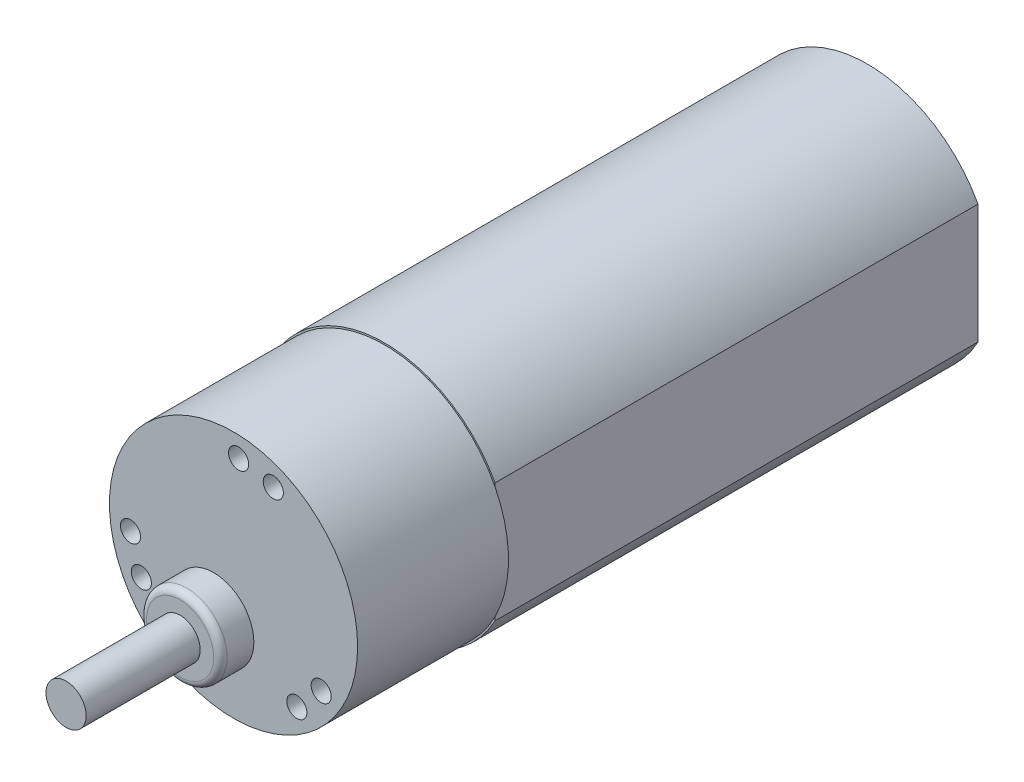
SolidWorks part; units mm, degrees
ref_plane "Front Plane" through (0, 0, 0) normal (0, 0, 1) x (1, 0, 0)
ref_plane "Top Plane" through (0, 0, 0) normal (0, 1, 0) x (1, 0, 0)
ref_plane "Right Plane" through (0, 0, 0) normal (1, 0, 0) x (0, 0, -1)
sketch "Sketch1" plane through (0, 0, 0) normal (0, 0, 1) x (1, 0, 0)
  line L0 (-16.5, 8.9058) -> (-16.5, -8.9058)
  line L1 (16.5, 8.9058) -> (16.5, -8.9058)
  arc A0 (-16.5, -8.9058) -> (16.5, -8.9058) centre (0, 0) ccw
  arc A1 (16.5, 8.9058) -> (-16.5, 8.9058) centre (0, 0) ccw
extrude "Boss-Extrude1" add sketch "Sketch1" along normal blind 72
sketch "Sketch2" plane through (0, 0, 72) normal (0, 0, 1) x (1, 0, 0)
  circle A0 centre (0, 0) radius 18.5
extrude "Boss-Extrude2" add sketch "Sketch2" along normal blind 22.5
sketch "Sketch3" plane through (0, 0, 94.5) normal (0, 0, 1) x (1, 0, 0)
  line L0 (0, 0) -> (-16.4075, -8.5466) construction
  line L1 (0.0271, -0.0522) -> (-13.7468, -7.1607) construction
  line L2 (0.0271, -0.0522) -> (0.7579, 15.4306) construction
  line L3 (0, 0) -> (-18.3411, -2.4195) construction
  line L4 (0, 0) -> (-15.3669, -2.0272) construction
  line L5 (-15.3669, -2.0272) -> (9.439, -12.2945) construction
  line L6 (5.9279, 14.3217) -> (-2.9639, -7.1608) construction
  circle A0 centre (0, 0) radius 18.5 construction
  circle A1 centre (-13.7468, -7.1607) radius 1.5
  circle A2 centre (0.7579, 15.4306) radius 1.5
  circle A3 centre (13.0701, -8.4265) radius 1.5
  circle A4 centre (-15.3669, -2.0272) radius 1.5
  circle A5 centre (5.9279, 14.3217) radius 1.5
  circle A6 centre (9.439, -12.2945) radius 1.5
  circle A7 centre (-2.9639, -7.1608) radius 6
  dimension "D1" = 3
  dimension "D6" = 3
  dimension "D3" = 120
  dimension "D4" = 15.5
  dimension "D5" = 20
  dimension "D8" = 15.5
  dimension "D2" = 3
  dimension "D7" = 3
extrude "Cut-Extrude1" cut sketch "Sketch3" against normal blind 5
sketch "Sketch4" plane through (0, 0, 89.5) normal (0, 0, 1) x (1, 0, 0)
  circle A0 centre (-2.9639, -7.1608) radius 6
extrude "Boss-Extrude3" add sketch "Sketch4" along normal blind 10
fillet "Fillet1" radius 1 1 edges at (3.0361, -7.1608, 99.5)
sketch "Sketch5" plane through (0, 0, 99.5) normal (0, 0, 1) x (1, 0, 0)
  circle A0 centre (-2.9639, -7.1608) radius 3
extrude "Boss-Extrude4" add sketch "Sketch5" along normal blind 17
sketch "Sketch6" plane through (-16.5, 0, 0) normal (-1, 0, 0) x (0, 0, 1)
  line L0 (72, -8.9058) -> (0, -8.9058) construction
  line L1 (0, 8.9058) -> (14.5455, 8.9058)
  line L2 (0, 8.9058) -> (0, -8.9058)
  line L3 (0, -8.9058) -> (14.5455, -8.9058)
  line L4 (14.5455, 8.9058) -> (14.5455, -8.9058)
extrude "Cut-Extrude2" cut sketch "Sketch6" against normal blind 7
sketch "Sketch7"
sketch_block_instance "Block2-1"
sketch_block "Block2"
sketch_block_instance "Block1-1"
sketch_block "Block1"
